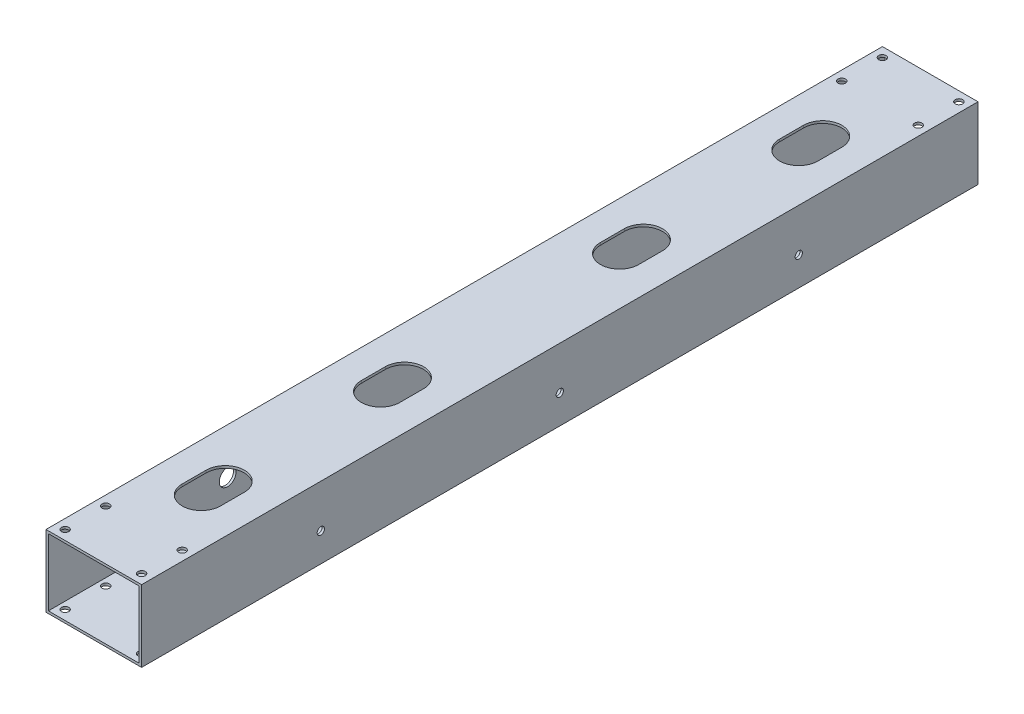
SolidWorks part; units mm, degrees
material "6063-T5"
ref_plane "前视基准面" through (0, 0, 0) normal (0, 0, 1) x (1, 0, 0)
ref_plane "上视基准面" through (0, 0, 0) normal (0, 1, 0) x (1, 0, 0)
ref_plane "右视基准面" through (0, 0, 0) normal (1, 0, 0) x (0, 0, -1)
sketch "草图1" plane through (0, 0, 0) normal (0, 0, 1) x (1, 0, 0)
  line L0 (-19, -14) -> (-19, 14)
  line L1 (-20, -15) -> (20, -15)
  line L2 (-20, -15) -> (-20, 15)
  line L3 (-20, 15) -> (20, 15)
  line L4 (20, -15) -> (20, 15)
  line L5 (0, 15) -> (0, -15) construction
  line L6 (-20, 0) -> (20, 0) construction
  line L7 (-19, 14) -> (19, 14)
  line L8 (19, -14) -> (19, 14)
  line L9 (-19, -14) -> (19, -14)
  point P0 (0, 0)
  dimension "D1" = 30
  dimension "D2" = 40
  dimension "D3" = 1
extrude "凸台-拉伸1" add sketch "草图1" along normal mid plane 350
sketch "草图2" plane through (20, 0, 0) normal (1, 0, 0) x (0, 0, -1)
  line L0 (0, -3) -> (0, 15) construction
  line L1 (-175, 15) -> (175, 15) construction
  circle A0 centre (0, -3) radius 1.525 construction
  circle A1 centre (-100, -3) radius 1.525 construction
  circle A2 centre (0, -3) radius 1.525
  circle A3 centre (-100, -3) radius 1.525
  circle A4 centre (100, -3) radius 1.525
extrude "切除-拉伸1" cut sketch "草图2" against normal blind 10
sketch "草图3" plane through (-19, 0, 0) normal (1, 0, 0) x (0, 0, -1)
  circle A0 centre (-100, -3) radius 3.5
  circle A1 centre (0, -3) radius 3.5
  circle A2 centre (100, -3) radius 3.5
  dimension "D1" = 7
extrude "切除-拉伸2" cut sketch "草图3" against normal blind 10
sketch "草图5" plane through (-20, 0, 0) normal (-1, 0, 0) x (0, 0, 1)
  circle A0 centre (125, -3) radius 1.525 construction
  circle A1 centre (-125, -3) radius 1.525 construction
  circle A2 centre (125, -3) radius 1.525
  circle A3 centre (-125, -3) radius 1.525
  circle A4 centre (-50, -3) radius 1.525 construction
  circle A5 centre (50, -3) radius 1.525 construction
  circle A6 centre (-50, -3) radius 1.525
  circle A7 centre (50, -3) radius 1.525
extrude "切除-拉伸3" cut sketch "草图5" against normal blind 10
sketch "草图6" plane through (0, -15, 0) normal (0, -1, 0) x (1, 0, 0)
  line L1 (-20, 51.525) -> (-20, 48.475) construction
  line L3 (-20, 126.525) -> (-20, 123.475) construction
  line L5 (-20, 51.525) -> (-20, 48.475) construction
  line L6 (-20, 126.525) -> (-20, 123.475) construction
  line L7 (-20, 125) -> (20, 125) construction
  line L8 (20, 175) -> (20, -175) construction
  line L9 (0, 120) -> (0, 130) construction
  line L10 (-8, 120) -> (-8, 130)
  line L11 (8, 120) -> (8, 130)
  line L12 (-20, 50) -> (20, 50) construction
  line L13 (0, 45) -> (0, 55) construction
  line L14 (-8, 45) -> (-8, 55)
  line L15 (8, 45) -> (8, 55)
  arc A0 (-8, 120) -> (8, 120) centre (0, 120) ccw
  arc A1 (8, 130) -> (-8, 130) centre (0, 130) ccw
  arc A2 (-8, 45) -> (8, 45) centre (0, 45) ccw
  arc A3 (8, 55) -> (-8, 55) centre (0, 55) ccw
  point P10 (0, 125)
  point P20 (0, 50)
  dimension "D2" = 8
  dimension "D1" = 10
extrude "切除-拉伸4" cut sketch "草图6" against normal blind 80
mirror "镜向1" about plane through (0, 0, 0) normal (0, 0, 1) of "切除-拉伸4"
sketch "草图7" plane through (0, 15, 0) normal (0, 1, 0) x (1, 0, 0)
  circle A0 centre (16, 171) radius 1.55 construction
  circle A1 centre (16, 154) radius 1.55 construction
  circle A2 centre (-16, 154) radius 1.55 construction
  circle A3 centre (-16, 171) radius 1.55 construction
  circle A4 centre (16, 171) radius 1.55
  circle A5 centre (16, 154) radius 1.55
  circle A6 centre (-16, 154) radius 1.55
  circle A7 centre (-16, 171) radius 1.55
extrude "切除-拉伸5" cut sketch "草图7" against normal blind 80
mirror "镜向2" about plane through (0, 0, 0) normal (0, 0, 1) of "切除-拉伸5"
